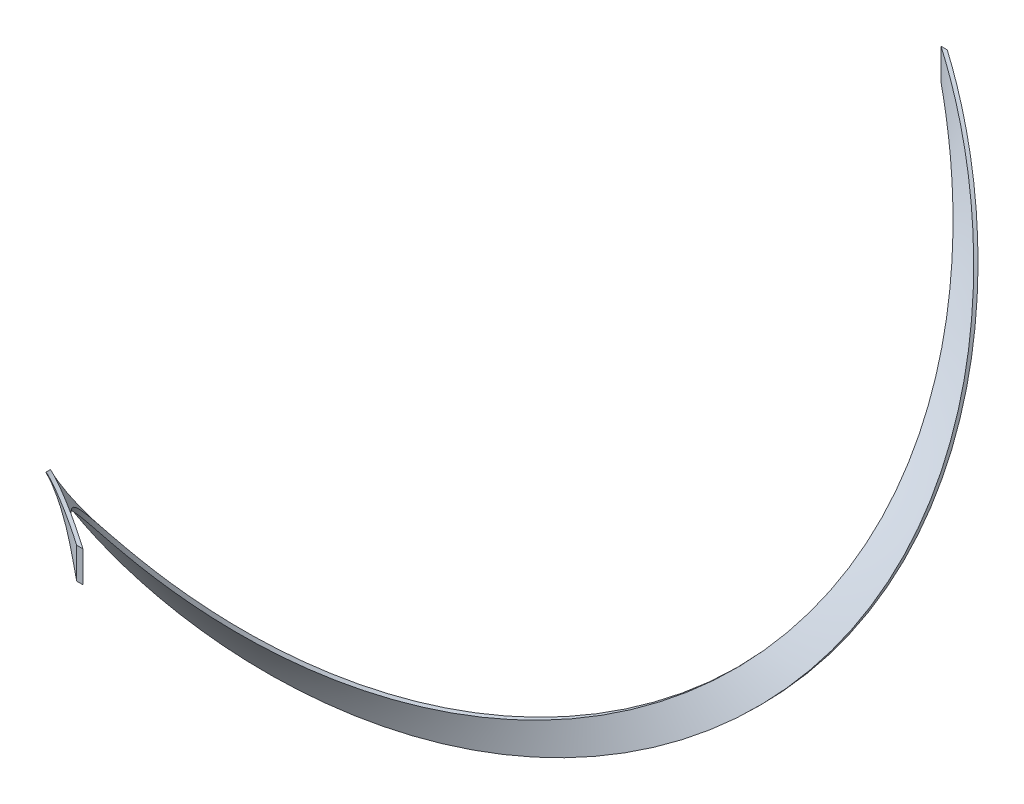
SolidWorks part; units mm, degrees
ref_plane "Front Plane" through (0, 0, 0) normal (0, 0, 1) x (1, 0, 0)
ref_plane "Top Plane" through (0, 0, 0) normal (0, 1, 0) x (1, 0, 0)
ref_plane "Right Plane" through (0, 0, 0) normal (1, 0, 0) x (0, 0, -1)
sketch "Sketch1" plane through (0, 0, 0) normal (0, 0, 1) x (1, 0, 0)
  line L0 (0, -190.5) -> (0, 190.5) construction
  circle A0 centre (0, 0) radius 190.5
  point P6 (0, 0)
  dimension "D1" = 381
curve "Helix/Spiral1" pitch 833 height 833 turns 1
sketch "Sketch2" plane through (0, 0, 0) normal (0, 0, 1) x (1, 0, 0)
  line L1 (-3, 190.4764) -> (3, 190.4764)
  line L2 (-3, 190.4764) -> (-3, 160.4764)
  line L3 (-3, 160.4764) -> (3, 160.4764)
  line L4 (3, 190.4764) -> (3, 160.4764)
  point P7 (0, 0)
  dimension "D1" = 6
  dimension "D2" = 30
sweep "Sweep1" add profiles "Sketch2" path "Helix/Spiral1"
